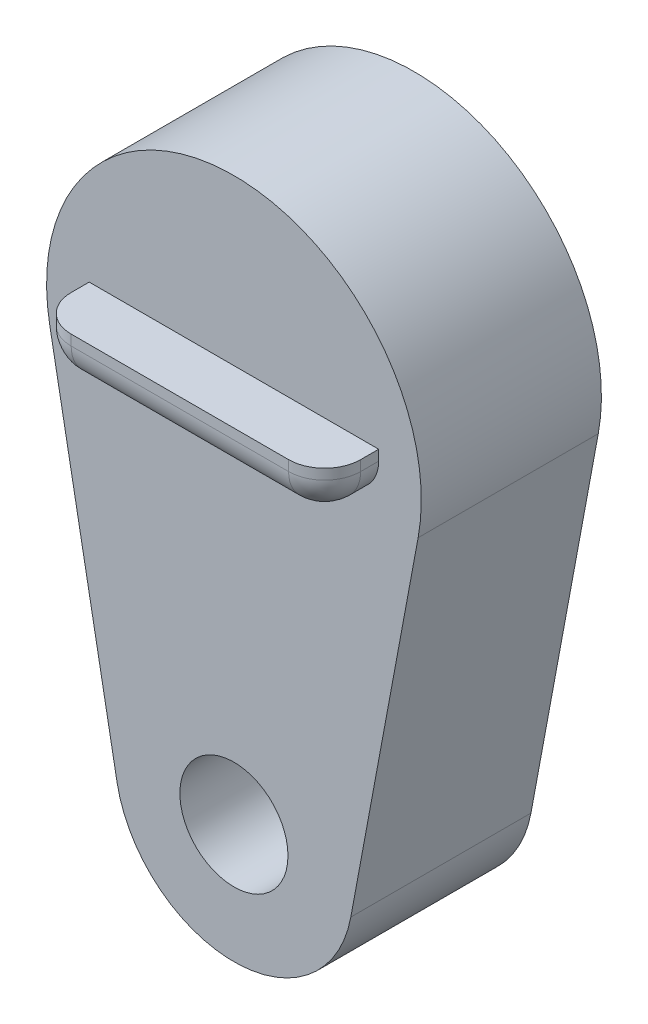
SolidWorks part; units mm, degrees
ref_plane "Front" through (0, 0, 0) normal (0, 0, 1) x (1, 0, 0)
ref_plane "Top" through (0, 0, 0) normal (0, 1, 0) x (1, 0, 0)
ref_plane "Right" through (0, 0, 0) normal (1, 0, 0) x (0, 0, -1)
sketch "Sketch1" plane through (0, 0, 0) normal (0, 0, 1) x (1, 0, 0)
  line L0 (0, 0) -> (0, 10.4) construction
  line L1 (-5.5991, 12.0685) -> (9129.0163, -49146.4384) construction
  line L2 (5.0052, 8.8725) -> (-9129.6102, -49149.6344) construction
  line L3 (-5.1125, 9.45) -> (-3.2445, -0.6029)
  line L4 (3.2445, -0.6029) -> (5.1125, 9.45)
  circle A0 centre (0, 0) radius 1.5
  arc A1 (-3.2445, -0.6029) -> (3.2445, -0.6029) centre (0, 0) ccw
  arc A2 (5.1125, 9.45) -> (-5.1125, 9.45) centre (0, 10.4) ccw
  dimension "D1" = 3
  dimension "D3" = 5.2
  dimension "D4" = 3.3
  dimension "D2" = 10.4
extrude "Boss-Extrude1" add sketch "Sketch1" along normal blind 5
sketch "Sketch2" plane through (0, 0, 5) normal (0, 0, 1) x (1, 0, 0)
  line L0 (0, -998.8927) -> (0, 49001.1073) construction
  line L1 (-3.0171, 9.7422) -> (3.0171, 9.7422)
  line L2 (-4.0171, 10.7422) -> (-4.0171, 11.0297)
  line L3 (-4.0171, 11.0297) -> (4.0171, 11.0297)
  line L4 (4.0171, 10.7422) -> (4.0171, 11.0297)
  line L5 (-4.0171, 9.7422) -> (4.0171, 11.0297) construction
  line L6 (-4.0171, 11.0297) -> (4.0171, 9.7422) construction
  arc A0 (3.0171, 9.7422) -> (4.0171, 10.7422) centre (3.0171, 10.7422) ccw
  arc A1 (-3.0171, 9.7422) -> (-4.0171, 10.7422) centre (-3.0171, 10.7422) cw
  point P0 (0, 10.3859)
  point P11 (0, 0)
  dimension "D1" = 1
extrude "Boss-Extrude2" add sketch "Sketch2" along normal blind 1.5
fillet "Fillet1" radius 1 5 edges at (-4.0171, 10.8859, 6.5) (-3.7242, 10.0351, 6.5) (4.0171, 10.8859, 6.5) (3.7242, 10.0351, 6.5) (0, 9.7422, 6.5)
